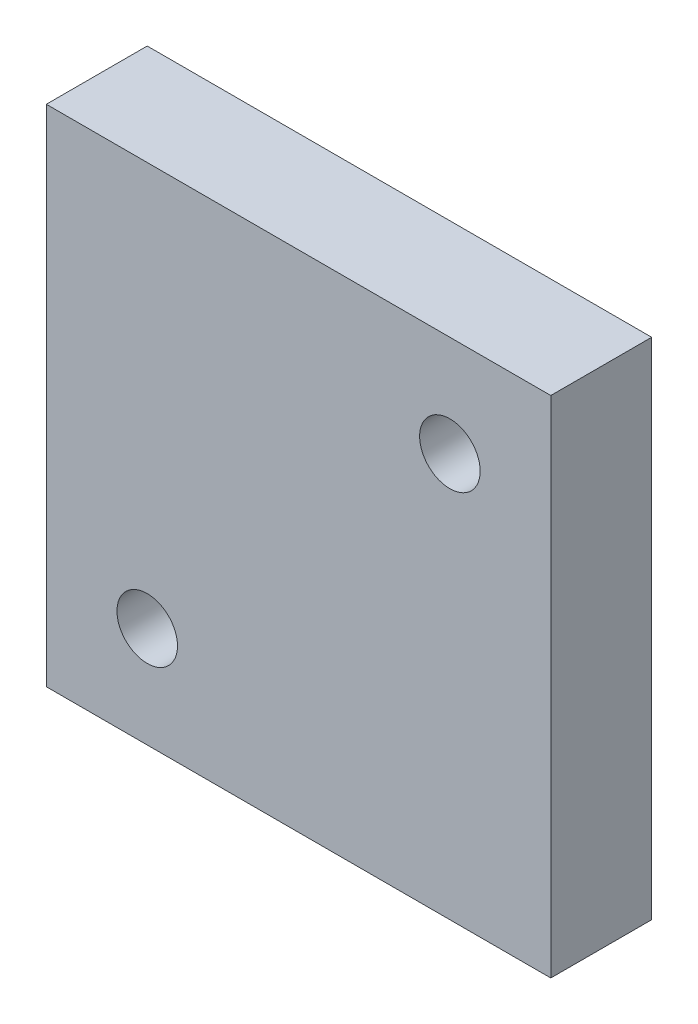
SolidWorks part; units mm, degrees
ref_plane "Front" through (0, 0, 0) normal (0, 0, 1) x (1, 0, 0)
ref_plane "Top" through (0, 0, 0) normal (0, 1, 0) x (1, 0, 0)
ref_plane "Right" through (0, 0, 0) normal (1, 0, 0) x (0, 0, -1)
sketch "Sketch1" plane through (0, 0, 0) normal (0, 0, 1) x (1, 0, 0)
  line L1 (0, 0) -> (100, 0)
  line L2 (0, 0) -> (0, 100)
  line L3 (0, 100) -> (100, 100)
  line L4 (100, 0) -> (100, 100)
  dimension "D1" = 100
  dimension "D2" = 100
extrude "Boss-Extrude1" add sketch "Sketch1" along normal blind 20
hole_wizard "Ø12.0 (12) Diameter Hole1" positions "Sketch3" profile "Sketch2" hole size "Ø12.0" standard "ISO" end condition through all
sketch "Sketch3" plane through (0, 0, 20) normal (0, 0, 1) x (1, 0, 0)
  line L0 (0, 100) -> (0, 0) construction
  line L1 (0, 0) -> (100, 0) construction
  point P0 (20, 20)
  point P2 (80, 80)
  dimension "D1" = 20
  dimension "D2" = 20
  dimension "D3" = 80
  dimension "D4" = 80
sketch "Sketch2" plane through (20, 20, 20) normal (1, 0, 0) x (0, -1, 0)
  line L0 (0, 0) -> (0, 20)
  line L1 (0, 20) -> (6, 20)
  line L2 (6, 20) -> (6, 0)
  line L5 (6, 0) -> (0, 0)
  line L11 (0, -6.35) -> (0, 107.95) construction
  dimension "Thru Hole Dia." = 12
  dimension "Thru Hole Depth" = 20
